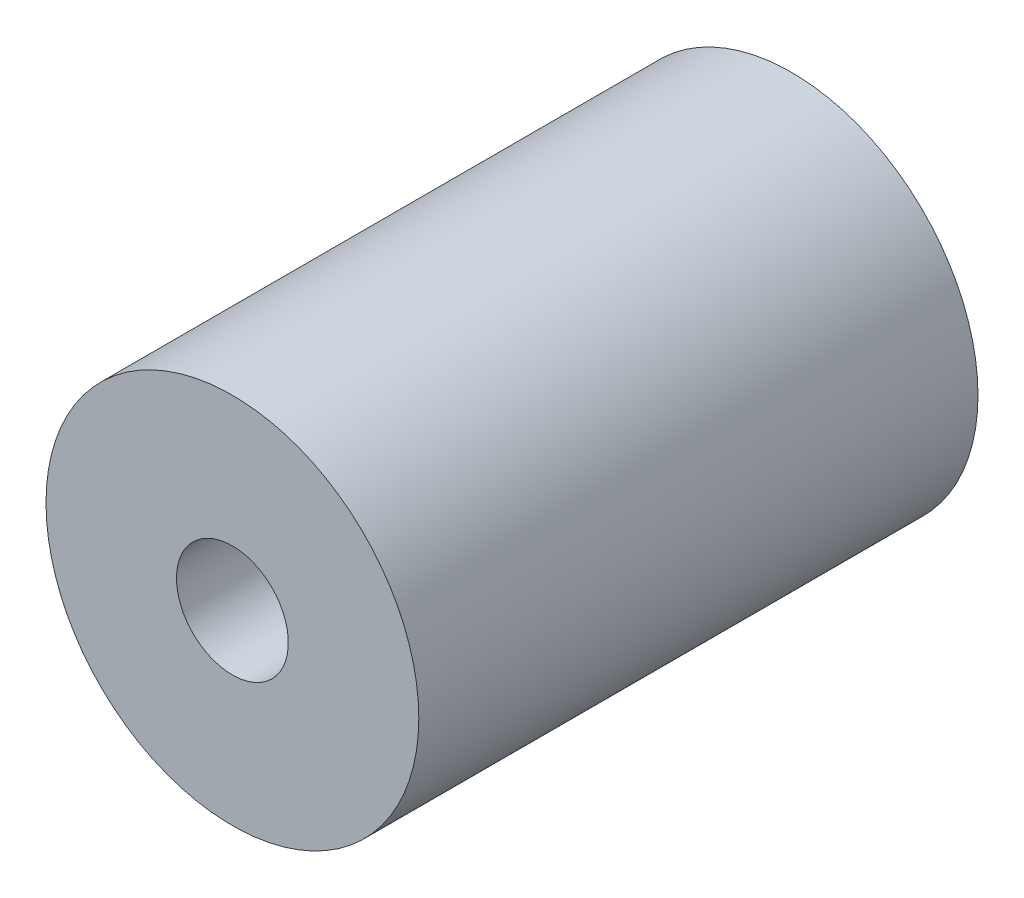
SolidWorks part; units mm, degrees
ref_plane "Ebene vorne" through (0, 0, 0) normal (0, 0, 1) x (1, 0, 0)
ref_plane "Ebene oben" through (0, 0, 0) normal (0, 1, 0) x (1, 0, 0)
ref_plane "Ebene rechts" through (0, 0, 0) normal (1, 0, 0) x (0, 0, -1)
sketch "Skizze1" plane through (0, 0, 0) normal (0, 0, 1) x (1, 0, 0)
  circle A0 centre (10.9493, -75.4975) radius 5
  dimension "D1" = 10
extrude "Aufsatz-Linear austragen1" add sketch "Skizze1" along normal blind 15 contours A0
hole_wizard "Ø1.5 (1.5) Durchmesser Bohrung1" positions "Skizze2" profile "Skizze3" hole size "Ø1.5" standard "DIN" end condition through all
sketch "Skizze2" plane through (0, 0, 15) normal (0, 0, 1) x (1, 0, 0)
  point P0 (10.9493, -75.4975)
sketch "Skizze3" plane through (10.9493, -75.4975, 15) normal (1, 0, 0) x (0, -1, 0)
  line L0 (0, 0) -> (0, 15)
  line L1 (0, 15) -> (0.75, 15)
  line L2 (0.75, 15) -> (0.75, 0)
  line L5 (0.75, 0) -> (0, 0)
  line L11 (0, -6.35) -> (0, 107.95) construction
  dimension "Bohrerdurchmesser" = 1.5
  dimension "Bohrungstiefe" = 15
hole_wizard "Ø3.0 (3) Durchmesser Bohrung1" positions "Skizze4" profile "Skizze6" hole size "Ø3.0" standard "DIN"
sketch "Skizze4" plane through (0, 0, 0) normal (0, 0, -1) x (-1, 0, 0)
  point P0 (-10.9493, -75.4975)
sketch "Skizze6" plane through (10.9493, -75.4975, 0) normal (1, 0, 0) x (0, 1, 0)
  line L0 (0, 0) -> (0, 15.9013)
  line L1 (0, 15.9013) -> (1.5, 15)
  line L2 (1.5, 15) -> (1.5, 0)
  line L5 (1.5, 0) -> (0, 0)
  line L10 (0, 15.9013) -> (-1.5, 15) construction
  line L11 (0, -6.35) -> (0, 107.95) construction
  dimension "Bohrerdurchmesser" = 3
  dimension "Bohrungstiefe" = 15
  dimension "Spitzenwinkel" = 118
